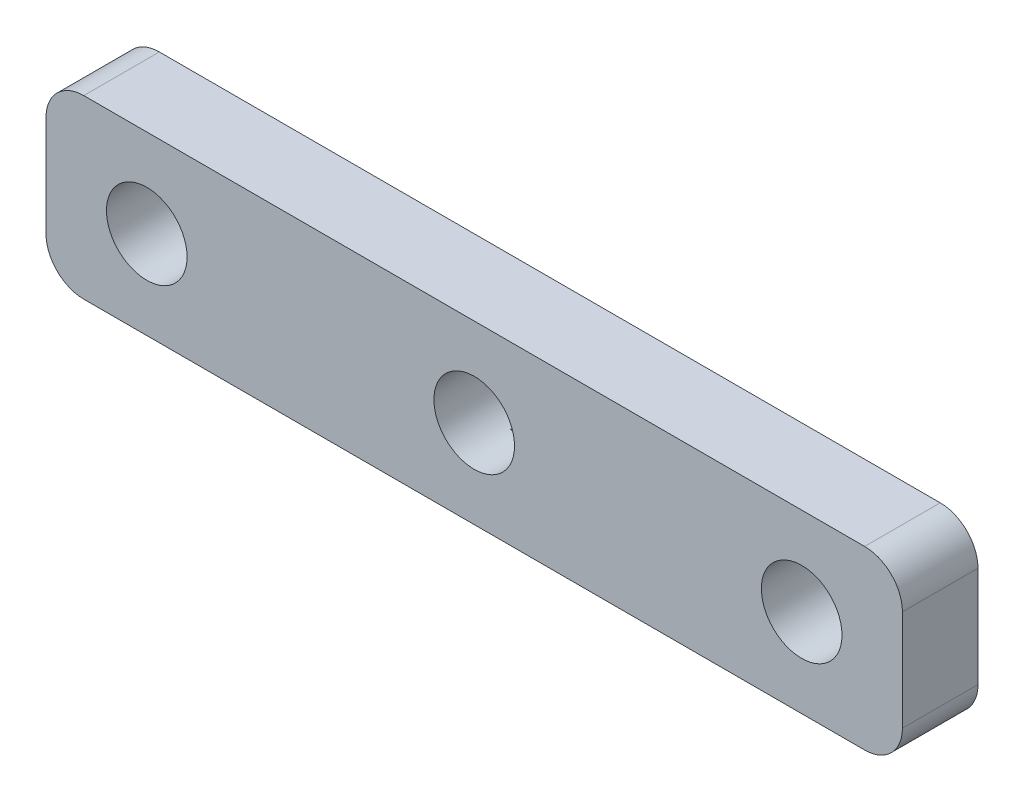
SolidWorks part; units mm, degrees
ref_plane "Front Plane" through (0, 0, 0) normal (0, 0, 1) x (1, 0, 0)
ref_plane "Top Plane" through (0, 0, 0) normal (0, 1, 0) x (1, 0, 0)
ref_plane "Right Plane" through (0, 0, 0) normal (1, 0, 0) x (0, 0, -1)
sketch "Sketch1" plane through (0, 0, 0) normal (0, 0, 1) x (1, 0, 0)
  line L0 (4, 3.5) -> (30, 3.5) construction
  line L1 (0, 0) -> (34, 0)
  line L2 (0, 0) -> (0, 7)
  line L3 (0, 7) -> (34, 7)
  line L4 (34, 0) -> (34, 7)
  line L5 (27.5, 37) -> (27.5, -3) construction
  circle A0 centre (4, 3.5) radius 1.6
  circle A1 centre (30, 3.5) radius 1.6
  circle A2 centre (17, 3.5) radius 1.6
  dimension "D5" = 3.2
  dimension "D1" = 6.5
  dimension "D2" = 7
  dimension "D3" = 26
extrude "Boss-Extrude1" add sketch "Sketch1" along normal blind 3
sketch "Sketch2" plane through (0, 0, 0) normal (0, 0, -1) x (-1, 0, 0)
  line L32 (-34, 7) -> (0, 7) construction
  line L33 (-26, 7) -> (-8, 7)
  line L34 (-26, 7) -> (-26, 8)
  line L40 (-26, 8) -> (-8, 8)
  line L41 (-8, 7) -> (-8, 8)
  line L42 (-26, 6) -> (-8, 6)
  line L43 (-26, 5) -> (-26, 6)
  line L44 (-26, 5) -> (-8, 5)
  line L45 (-8, 5) -> (-8, 6)
  line L46 (-26, 4) -> (-8, 4)
  line L47 (-26, 3) -> (-26, 4)
  line L48 (-26, 3) -> (-8, 3)
  line L49 (-8, 3) -> (-8, 4)
  line L50 (-26, 2) -> (-8, 2)
  line L51 (-26, 1) -> (-26, 2)
  line L52 (-26, 1) -> (-8, 1)
  line L53 (-8, 1) -> (-8, 2)
  line L54 (-26, 0) -> (-8, 0)
  line L55 (-26, -1) -> (-26, 0)
  line L56 (-26, -1) -> (-8, -1)
  line L57 (-8, -1) -> (-8, 0)
  line L58 (0, 7) -> (0, 0) construction
  line L59 (-34, 0) -> (-34, 7) construction
  point P6 (-8, 7.5)
  dimension "D1" = 1
  dimension "D2" = 5
  dimension "D3" = 8
  dimension "D4" = 8
extrude "Cut-Extrude1" cut sketch "Sketch2" against normal blind 1
fillet "Fillet1" radius 1.5 4 edges at (0, 0, 1.5) (0, 7, 1.5) (34, 0, 1.5) (34, 7, 1.5)
